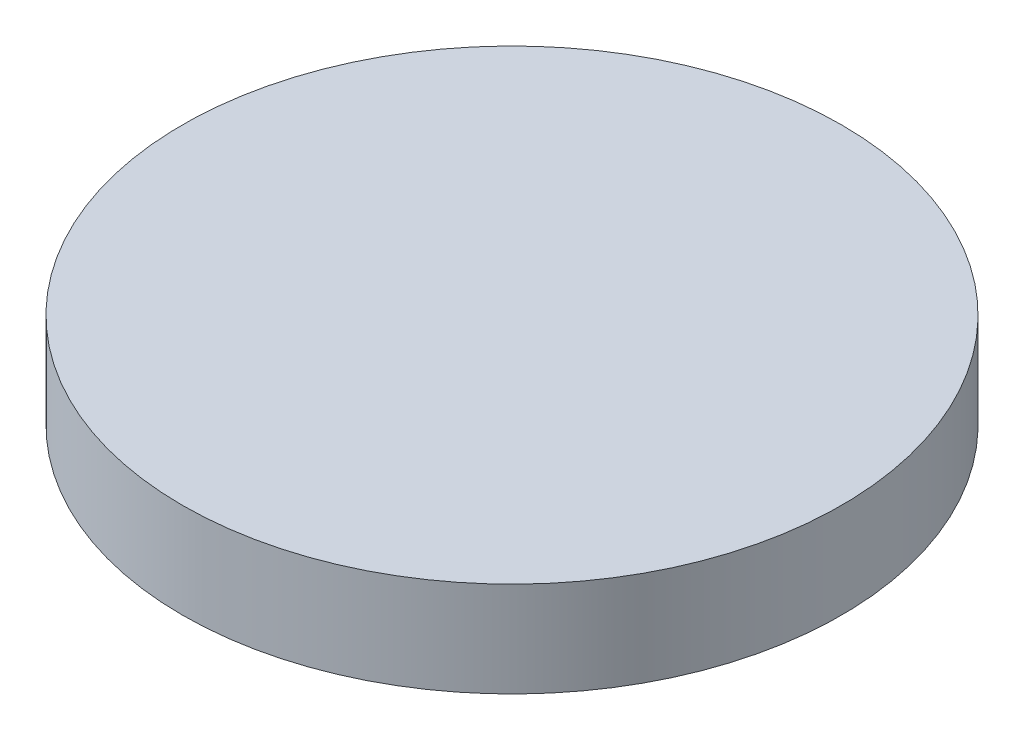
SolidWorks part; units mm, degrees
ref_plane "Front Plane" through (0, 0, 0) normal (0, 0, 1) x (1, 0, 0)
ref_plane "Top Plane" through (0, 0, 0) normal (0, 1, 0) x (1, 0, 0)
ref_plane "Right Plane" through (0, 0, 0) normal (1, 0, 0) x (0, 0, -1)
sketch "Sketch1" plane through (0, 0, 0) normal (0, 1, 0) x (1, 0, 0)
  circle A0 centre (0, 0) radius 5.5
  dimension "D1" = 11
extrude "Boss-Extrude1" add sketch "Sketch1" along normal blind 1.5875
other "Freeze***"
